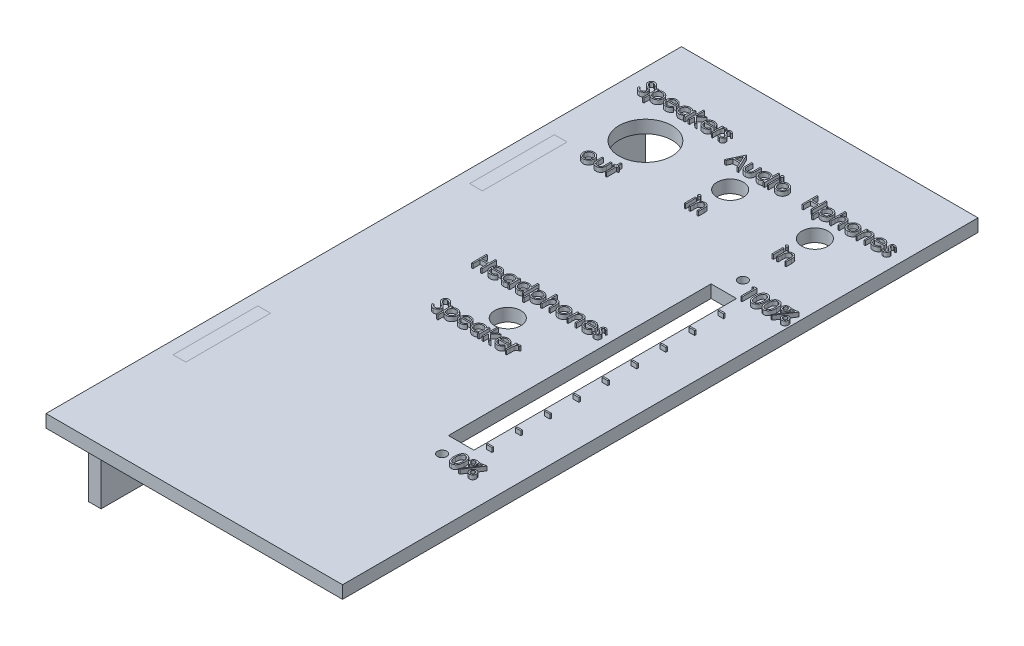
SolidWorks part; units mm, degrees
ref_plane "Front Plane" through (0, 0, 0) normal (0, 0, 1) x (1, 0, 0)
ref_plane "Top Plane" through (0, 0, 0) normal (0, 1, 0) x (1, 0, 0)
ref_plane "Right Plane" through (0, 0, 0) normal (1, 0, 0) x (0, 0, -1)
sketch "Sketch1" plane through (0, 0, 0) normal (0, 1, 0) x (1, 0, 0)
  line L0 (0, -23.5) -> (50000, -23.5) construction
  line L1 (0, 0) -> (70, 0)
  line L2 (0, 0) -> (0, -150)
  line L3 (0, -150) -> (70, -150)
  line L4 (70, 0) -> (70, -150)
  line L5 (55, -13.7802) -> (55, -50013.7802) construction
  line L6 (55, -76) -> (50055, -76) construction
  line L7 (58, -45) -> (52, -45)
  line L8 (58, -45) -> (58, -107)
  line L9 (58, -107) -> (52, -107)
  line L10 (52, -45) -> (52, -107)
  line L11 (58, -45) -> (52, -107) construction
  line L12 (58, -107) -> (52, -45) construction
  line L14 (3, -123) -> (6, -123)
  line L15 (3, -123) -> (3, -103)
  line L16 (3, -103) -> (6, -103)
  line L17 (6, -123) -> (6, -103)
  line L18 (3, -33) -> (6, -33)
  line L19 (3, -33) -> (3, -53)
  line L20 (3, -53) -> (6, -53)
  line L21 (6, -33) -> (6, -53)
  circle A0 centre (15, -23.5) radius 6.25
  circle A1 centre (35, -23.5) radius 3.1
  circle A2 centre (55, -23.5) radius 3.1
  circle A3 centre (55, -40.5) radius 1.1
  circle A4 centre (55, -111.5) radius 1.1
  circle A5 centre (35, -76) radius 3.1
  point P13 (55, -76)
  dimension "D2" = 12.5
  dimension "D5" = 6.2
  dimension "D10" = 2.2
  dimension "D11" = 2.2
  dimension "D14" = 6.2
  dimension "D16" = 20
  dimension "D1" = 150
  dimension "D3" = 15
  dimension "D4" = 62
  dimension "D6" = 20
  dimension "D7" = 20
  dimension "D8" = 23.5
  dimension "D9" = 6
  dimension "D12" = 71
  dimension "D13" = 4.5
  dimension "D15" = 55
  dimension "D17" = 70
  dimension "D18" = 45
  dimension "D19" = 20
  dimension "D20" = 3
  dimension "D21" = 50
  dimension "D22" = 33
  dimension "D23" = 3
  dimension "D24" = 3
extrude "Boss-Extrude1" add sketch "Sketch1" along normal blind 3
ref_plane "Plane1" through (3, 0, 0) normal (1, 0, 0) x (0, 0, -1)
sketch "Sketch3" plane through (3, 0, 0) normal (1, 0, 0) x (0, 0, -1)
  line L0 (-143, -17) -> (-14.476, -17)
  line L1 (-14.476, -17) -> (-14.476, 0)
  line L2 (-150, 0) -> (0, 0) construction
  line L3 (-143, -17) -> (-143, 0)
  line L4 (-14.476, 0) -> (-33, 0)
  line L5 (-33, 0) -> (-33, 3)
  line L6 (-150, 3) -> (0, 3) construction
  line L7 (-33, 3) -> (-53, 3)
  line L8 (-53, 3) -> (-53, 0)
  line L9 (-150, 3) -> (-150, 0) construction
  line L10 (-143, 0) -> (-123, 0)
  line L11 (-123, 0) -> (-123, 3)
  line L12 (-123, 3) -> (-103, 3)
  line L13 (-103, 3) -> (-103, 0)
  line L14 (-103, 0) -> (-53, 0)
  line L15 (-143, -3.81) -> (49857, -3.81) construction
  circle A0 centre (-136.65, -3.81) radius 1.6
  circle A1 centre (-89.342, -3.81) radius 1.6
  circle A2 centre (-42.035, -3.81) radius 1.6
  point P15 (-150, 1.5)
  dimension "D7" = 3.2
  dimension "D1" = 128.524
  dimension "D2" = 17
  dimension "D3" = 20
  dimension "D4" = 7
  dimension "D5" = 20
  dimension "D6" = 3.81
  dimension "D8" = 6.35
  dimension "D9" = 47.308
  dimension "D10" = 47.307
extrude "Boss-Extrude2" add sketch "Sketch3" along normal blind 3 and the other way blind 0.0001 separate body
sketch "Sketch4" plane through (0, 3, 0) normal (0, 1, 0) x (1, 0, 0)
  line L1 (0, 0) -> (0, -150) construction
  line L2 (70, 0) -> (0, 0) construction
  text T0 "Speakers\r\n\r\n\r\n     out" font "Century Gothic" height 3.5
  text T1 "Audio \r\n\r\n   in"
  text T2 "Hphones\r\n\r\n     in"
  text T3 "Headphones\r\n\r\n   Speaker"
  text T4 "100%\r\n -\r\n -\r\n -\r\n -\r\n -\r\n -\r\n -\r\n -\r\n -\r\n0%"
  dimension "D1" = 4
  dimension "D2" = 15
  dimension "D3" = 19
  dimension "D4" = 29
  dimension "D5" = 47
  dimension "D6" = 19
  dimension "D7" = 20
  dimension "D8" = 70
  dimension "D9" = 57.8
  dimension "D10" = 45
extrude "Boss-Extrude3" add sketch "Sketch4" along normal blind 1 separate body
